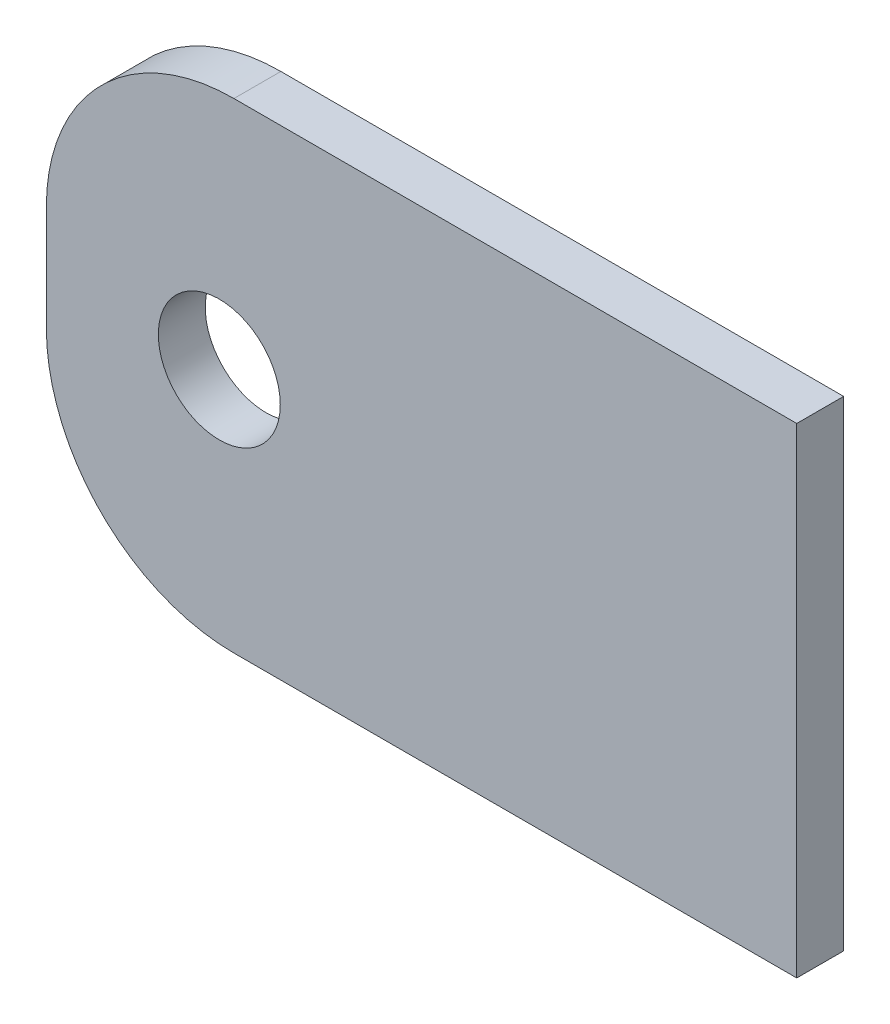
SolidWorks part; units mm, degrees
ref_plane "Front Plane" through (0, 0, 0) normal (0, 0, 1) x (1, 0, 0)
ref_plane "Top Plane" through (0, 0, 0) normal (0, 1, 0) x (1, 0, 0)
ref_plane "Right Plane" through (0, 0, 0) normal (1, 0, 0) x (0, 0, -1)
sketch "Sketch2" plane through (0, 0, 0) normal (0, 0, 1) x (1, 0, 0)
  line L0 (-11.2188, 3.0921) -> (18.7812, 3.0921)
  line L1 (18.7812, 3.0921) -> (18.7812, -22.5079)
  line L2 (-21.2188, -6.9079) -> (-21.2188, -12.5079)
  line L3 (-11.2188, -22.5079) -> (18.7812, -22.5079)
  line L4 (-24.9235, -9.8079) -> (22.4651, -9.8079) construction
  line L5 (-1.2188, 7.5613) -> (-1.2188, -25.9592) construction
  circle A2 centre (-12, -9.8079) radius 3.25
  arc A3 (-21.2188, -12.5079) -> (-11.2188, -22.5079) centre (-11.2188, -12.5079) ccw
  arc A4 (-21.2188, -6.9079) -> (-11.2188, 3.0921) centre (-11.2188, -6.9079) cw
  point P9 (-21.2188, -9.7079)
  point P10 (-19.3388, 3.0921)
  point P18 (18.7812, -9.7079)
  point P19 (0, 0)
  dimension "D3" = 10
  dimension "D4" = 6.5
  dimension "D1" = 38.12
  dimension "D2" = 25.6
  dimension "D6" = 20
  dimension "D7" = 40
extrude "Boss-Extrude1" add sketch "Sketch2" along normal blind 2.5
